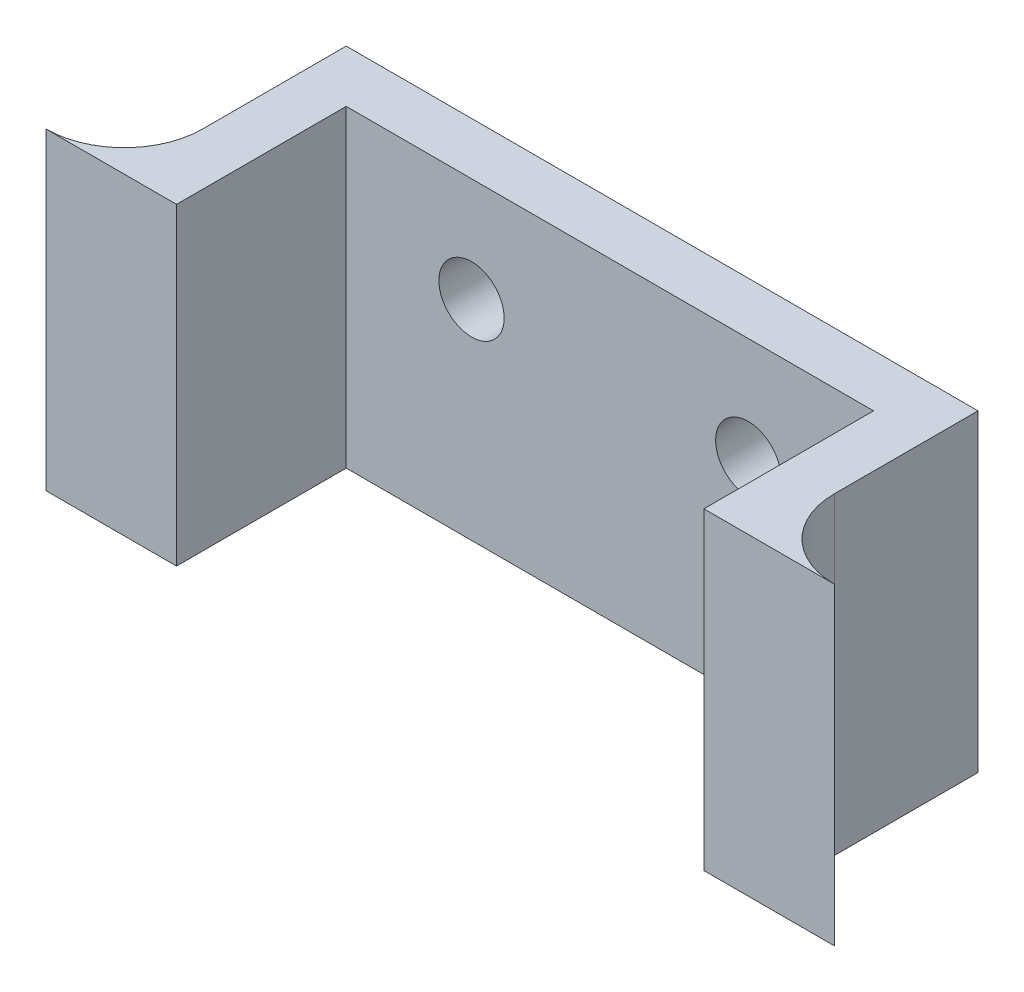
SolidWorks part; units mm, degrees
ref_plane "Plan de face" through (0, 0, 0) normal (0, 0, 1) x (1, 0, 0)
ref_plane "Plan de dessus" through (0, 0, 0) normal (0, 1, 0) x (1, 0, 0)
ref_plane "Plan de droite" through (0, 0, 0) normal (1, 0, 0) x (0, 0, -1)
sketch "Esquisse1" plane through (0, 0, 0) normal (0, 1, 0) x (1, 0, 0)
  line L0 (-10.1, 3.25) -> (-10.1, -3.25)
  line L2 (10.1, -3.25) -> (10.1, 3.25)
  line L3 (10.1, 3.25) -> (-10.1, 3.25)
  line L4 (-12.1, 5.25) -> (12.1, 5.25)
  line L8 (-12.1, 5.25) -> (-12.1, -0.25)
  line L9 (-12.1, -3.25) -> (-10.1, -3.25)
  line L10 (0, 0) -> (0, -5.7195) construction
  line L11 (12.1, 5.25) -> (12.1, -0.25)
  line L12 (12.1, -3.25) -> (10.1, -3.25)
  line L13 (-15.1, -3.25) -> (-12.1, -3.25)
  line L14 (12.1, -3.25) -> (15.1, -3.25)
  arc A0 (-12.1, -0.25) -> (-15.1, -3.25) centre (-15.1, -0.25) cw
  arc A1 (15.1, -3.25) -> (12.1, -0.25) centre (15.1, -0.25) cw
  dimension "D3" = 3
  dimension "D4" = 3
  dimension "D1" = 2
  dimension "D5" = 20.2
  dimension "D6" = 6.5
  dimension "D2" = 10.1
  dimension "D7" = 2
extrude "Boss.-Extru.1" add sketch "Esquisse1" along normal blind 12
sketch "Esquisse3" plane through (0, 0, -5.25) normal (0, 0, -1) x (-1, 0, 0)
  line L0 (0, 0) -> (0, 12.5794) construction
  line L1 (-12.1, 0) -> (12.1, 0) construction
  circle A0 centre (-5.3, 8) radius 1.25
  circle A2 centre (5.3, 8) radius 1.25
  dimension "D1" = 2.5
  dimension "D2" = 5.3
  dimension "D3" = 8
extrude "Enlèv. mat.-Extru.1" cut sketch "Esquisse3" against normal up to next
equation "\"D2@Esquisse1\"=\"D5@Esquisse1\"/2"
equation "\"D7@Esquisse1\"=\"D1@Esquisse1\""
